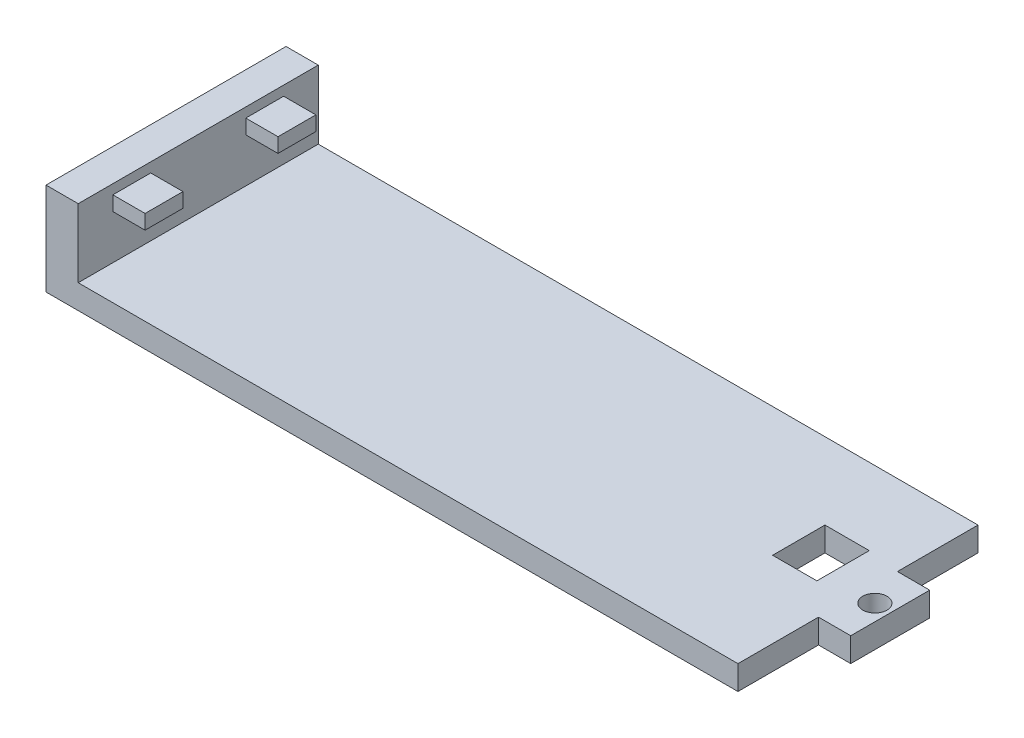
SolidWorks part; units mm, degrees
ref_plane "Front Plane" through (0, 0, 0) normal (0, 0, 1) x (1, 0, 0)
ref_plane "Top Plane" through (0, 0, 0) normal (0, 1, 0) x (1, 0, 0)
ref_plane "Right Plane" through (0, 0, 0) normal (1, 0, 0) x (0, 0, -1)
sketch "Sketch1" plane through (0, 0, 0) normal (0, 1, 0) x (1, 0, 0)
  line L2 (0, 0) -> (89.9, 0)
  line L3 (89.9, 0) -> (89.9, 29.8)
  line L4 (0, 29.8) -> (89.9, 29.8)
  line L5 (0, 29.8) -> (0, 0)
  dimension "D1" = 29.8
  dimension "D3" = 89.9
extrude "Boss-Extrude1" add sketch "Sketch1" along normal blind 3
sketch "Sketch8" plane through (0, 0, 0) normal (0, -1, 0) x (-1, 0, 0)
  line L0 (-89.9, 0) -> (-89.9, 29.8) construction
  line L1 (-89.9, 0) -> (-85.9, 0)
  line L2 (-89.9, 0) -> (-89.9, 10)
  line L3 (-89.9, 10) -> (-85.9, 10)
  line L4 (-85.9, 0) -> (-85.9, 10)
  line L5 (-89.9, 29.8) -> (-85.9, 29.8)
  line L6 (-89.9, 29.8) -> (-89.9, 19.8)
  line L7 (-89.9, 19.8) -> (-85.9, 19.8)
  line L8 (-85.9, 29.8) -> (-85.9, 19.8)
  circle A0 centre (-87.9, 15) radius 1.5
  dimension "D7" = 3
  dimension "D1" = 10
  dimension "D2" = 10
  dimension "D3" = 4
  dimension "D4" = 4
  dimension "D5" = 2
  dimension "D6" = 5
extrude "Cut-Extrude5" cut sketch "Sketch8" against normal blind 5
sketch "Sketch12" plane through (0, 0, 0) normal (0, -1, 0) x (1, 0, 0)
  line L1 (76.4, -13.8) -> (81.9, -13.8)
  line L2 (76.4, -13.8) -> (76.4, -20.3)
  line L3 (76.4, -20.3) -> (81.9, -20.3)
  line L4 (81.9, -13.8) -> (81.9, -20.3)
  line L5 (89.9, -10) -> (89.9, -19.8) construction
  line L8 (0, 0) -> (85.9, 0) construction
  dimension "D1" = 6.5
  dimension "D2" = 5.5
  dimension "D3" = 8
  dimension "D4" = 13.8
extrude "Cut-Extrude8" cut sketch "Sketch12" against normal blind 10
sketch "Sketch15" plane through (0, 3, 0) normal (0, 1, 0) x (1, 0, 0)
  line L0 (0, 0) -> (85.9, 0) construction
  line L1 (0, 29.8) -> (4, 29.8)
  line L2 (0, 29.8) -> (0, 0)
  line L3 (0, 0) -> (4, 0)
  line L4 (4, 29.8) -> (4, 0)
  dimension "D1" = 4
extrude "Boss-Extrude2" add sketch "Sketch15" along normal blind 8.5
sketch "Sketch16" plane through (4, 0, 0) normal (1, 0, 0) x (0, 0, -1)
  line L0 (29.8, 11.5) -> (29.8, 3) construction
  line L1 (4.3, 8.5) -> (9, 8.5)
  line L2 (4.3, 8.5) -> (4.3, 10.3)
  line L3 (4.3, 10.3) -> (9, 10.3)
  line L4 (9, 8.5) -> (9, 10.3)
  line L5 (20.8, 8.5) -> (25.5, 8.5)
  line L6 (20.8, 8.5) -> (20.8, 10.3)
  line L7 (20.8, 10.3) -> (25.5, 10.3)
  line L8 (25.5, 8.5) -> (25.5, 10.3)
  line L9 (0, 11.5) -> (0, 3) construction
  line L10 (0, 11.5) -> (29.8, 11.5) construction
  dimension "D1" = 4.3
  dimension "D2" = 4.3
  dimension "D3" = 4.7
  dimension "D4" = 4.7
  dimension "D5" = 1.8
  dimension "D6" = 1.8
  dimension "D7" = 1.2
  dimension "D8" = 1.2
extrude "Boss-Extrude3" add sketch "Sketch16" along normal blind 4
